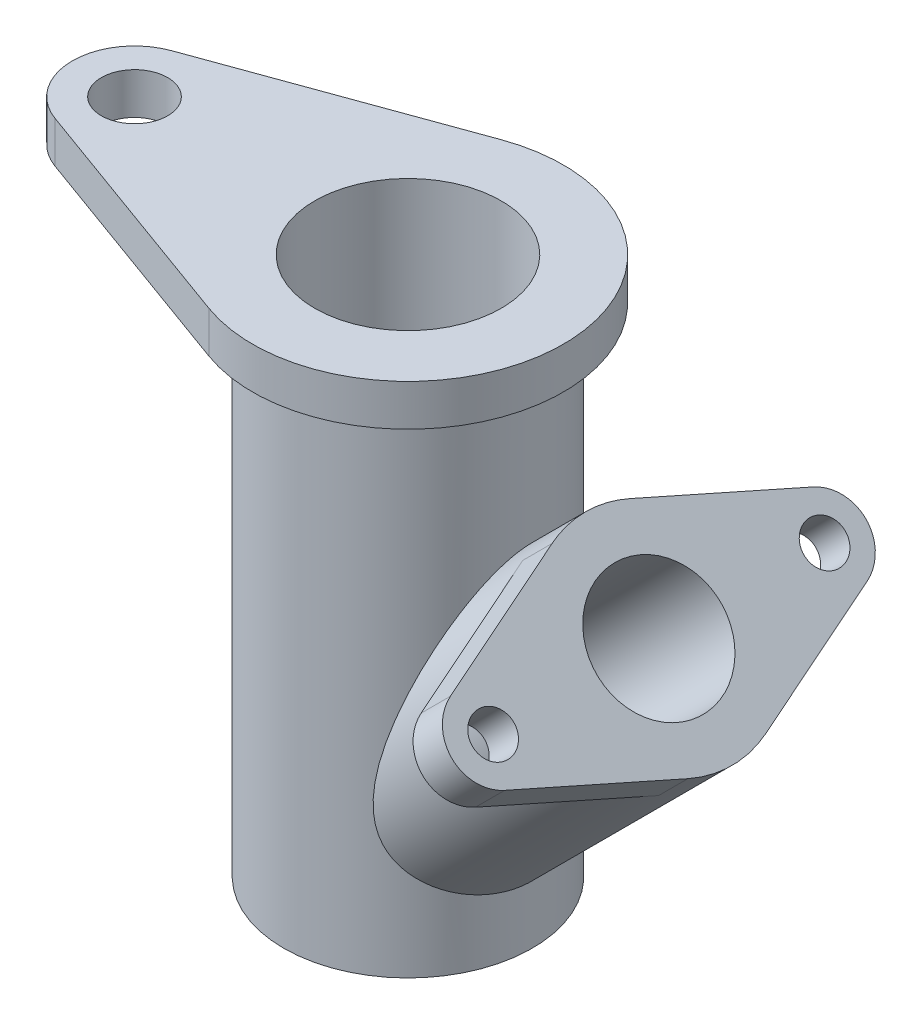
SolidWorks part; units mm, degrees
ref_plane "前视基准面" through (0, 0, 0) normal (0, 0, 1) x (1, 0, 0)
ref_plane "上视基准面" through (0, 0, 0) normal (0, 1, 0) x (1, 0, 0)
ref_plane "右视基准面" through (0, 0, 0) normal (1, 0, 0) x (0, 0, -1)
other "Configuration Table"
sketch "草图1" plane through (0, 0, 0) normal (0, 1, 0) x (1, 0, 0)
  circle A0 centre (0, 0) radius 60
  dimension "D1" = 120
extrude "凸台-拉伸1" add sketch "草图1" along normal blind 240
sketch "草图2" plane through (0, 240, 0) normal (0, 1, 0) x (1, 0, 0)
  line L2 (-142.2273, 28.2029) -> (-25.5682, 70.5072)
  line L3 (-132, 0) -> (0, 0) construction
  line L4 (-142.2273, -28.2029) -> (-25.5682, -70.5072)
  circle A1 centre (-132, 0) radius 16
  arc A5 (-25.5682, -70.5072) -> (-25.5682, 70.5072) centre (0, 0) ccw
  arc A6 (-142.2273, 28.2029) -> (-142.2273, -28.2029) centre (-132, 0) ccw
  dimension "D1" = 132
  dimension "D2" = 32
  dimension "D4" = 60
  dimension "D3" = 150
sketch "草图3" plane through (0, 240, 0) normal (0, 1, 0) x (1, 0, 0)
extrude "凸台-拉伸2" add sketch "草图2" along normal blind 20
sketch "草图6" plane through (0, 260, 0) normal (0, 1, 0) x (1, 0, 0)
  circle A0 centre (0, 0) radius 45
  dimension "D1" = 90
extrude "切除-拉伸1" cut sketch "草图6" against normal through all both and the other way through all
sketch "草图4" plane through (0, 0, 0) normal (0, 0, 1) x (1, 0, 0)
  line L0 (36.7731, 75.6741) -> (121.099, 160) construction
  line L1 (-60, 0) -> (60, 0) construction
  dimension "D1" = 160
  dimension "D2" = 45
ref_plane "基准面2" through (121.099, 160, 0) normal (0.7071, 0.7071, 0) x (0.7071, -0.7071, 0)
sketch "草图5" plane through (121.099, 160, 0) normal (0.7071, 0.7071, 0) x (0.7071, -0.7071, 0)
  circle A0 centre (0, 0) radius 50
  circle A1 centre (0, 0) radius 30
  dimension "D1" = 100
  dimension "D2" = 60
extrude "凸台-拉伸3" add sketch "草图5" against normal up to next
sketch "草图8" plane through (140.5495, 140.5495, 0) normal (0.7071, 0.7071, 0) x (0, 0, -1)
  circle A0 centre (0, 27.5072) radius 30 construction
  circle A1 centre (0, 27.5072) radius 30
extrude "切除-拉伸2" cut sketch "草图8" against normal up to surface and the other way through all up to face at (0, 260, 45)
sketch "草图9" plane through (140.5495, 140.5495, 0) normal (0.7071, 0.7071, 0) x (0, 0, -1)
  line L0 (0, 27.5072) -> (0, 103.287) construction
  line L1 (211.7544, 27.5072) -> (70, 27.5072) construction
  line L2 (-87.5, 46.0477) -> (-18.75, 73.8584)
  line L3 (18.75, 73.8584) -> (87.5, 46.0477)
  line L4 (18.75, -18.844) -> (87.5, 8.9667)
  line L5 (-87.5, 8.9667) -> (-18.75, -18.844)
  line L6 (-50, 27.5072) -> (-60, 27.5072) construction
  line L7 (60, 27.5072) -> (50, 27.5072) construction
  line L8 (-70, 27.5072) -> (-257.642, 27.5072) construction
  circle A0 centre (-80, 27.5072) radius 10
  arc A1 (-87.5, 46.0477) -> (-87.5, 8.9667) centre (-80, 27.5072) ccw
  circle A2 centre (80, 27.5072) radius 10
  arc A3 (87.5, 8.9667) -> (87.5, 46.0477) centre (80, 27.5072) ccw
  circle A4 centre (0, 27.5072) radius 50 construction
  arc A5 (-18.75, -18.844) -> (18.75, -18.844) centre (0, 27.5072) ccw
  arc A6 (18.75, 73.8584) -> (-18.75, 73.8584) centre (0, 27.5072) ccw
  circle A7 centre (0, 27.5072) radius 30
  dimension "D1" = 20
  dimension "D2" = 40
  dimension "D3" = 40
  dimension "D4" = 20
  dimension "D5" = 80
  dimension "D6" = 80
extrude "凸台-拉伸4" add sketch "草图9" against normal blind 20
